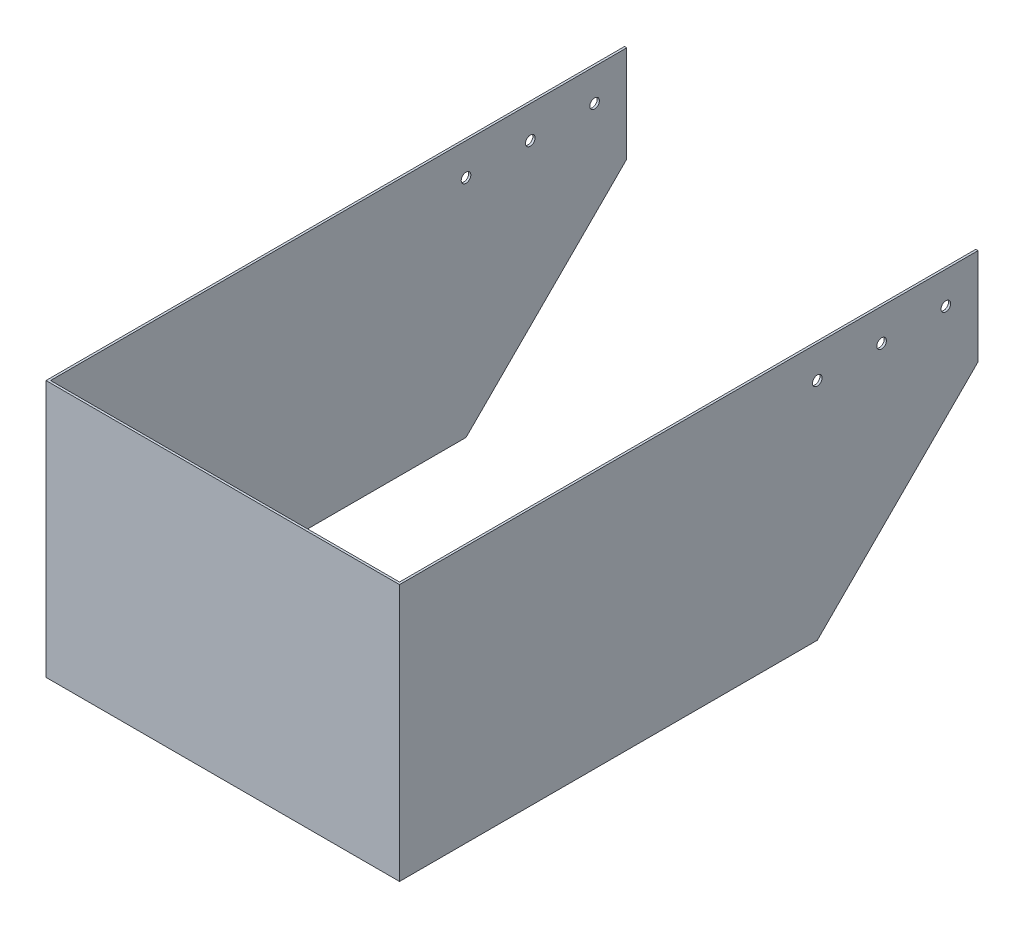
SolidWorks part; units mm, degrees
ref_plane "Front Plane" through (0, 0, 0) normal (0, 0, 1) x (1, 0, 0)
ref_plane "Top Plane" through (0, 0, 0) normal (0, 1, 0) x (1, 0, 0)
ref_plane "Right Plane" through (0, 0, 0) normal (1, 0, 0) x (0, 0, -1)
sketch "Sketch1" plane through (0, 0, 0) normal (0, 1, 0) x (1, 0, 0)
  line L1 (0, 0) -> (110, 0)
  line L2 (0, 0) -> (0, 180)
  line L3 (0, 180) -> (110, 180)
  line L4 (110, 0) -> (110, 180)
  dimension "D1" = 110
  dimension "D2" = 180
extrude "Boss-Extrude1" add sketch "Sketch1" along normal blind 80
sketch "Sketch2" plane through (0, 80, 0) normal (0, 1, 0) x (1, 0, 0)
  line L0 (110, 180) -> (0, 180) construction
  line L1 (0.7, 180) -> (109.3, 180)
  line L2 (0.7, 180) -> (0.7, 0.7)
  line L3 (0.7, 0.7) -> (109.3, 0.7)
  line L4 (109.3, 180) -> (109.3, 0.7)
  line L6 (0, 0) -> (110, 0) construction
  line L7 (0, 180) -> (0, 0) construction
  line L8 (110, 0) -> (110, 180) construction
  dimension "D1" = 0.7
  dimension "D2" = 0.7
  dimension "D3" = 0.7
extrude "Cut-Extrude1" cut sketch "Sketch2" against normal through all
sketch "Sketch4" plane through (110, 0, 0) normal (1, 0, 0) x (0, 0, -1)
  line L0 (0, 80) -> (180, 80) construction
  line L1 (180, 80) -> (180, 0) construction
  line L2 (170, 70) -> (139.2817, 70) construction
  circle A0 centre (170, 70) radius 1.5
  circle A1 centre (130, 70) radius 1.5
  circle A2 centre (150, 70) radius 1.5
  point P12 (0, 0)
  point P13 (0, 0)
  point P14 (0, 0)
  point P15 (0, 0)
  dimension "D2" = 3
  dimension "D4" = 20
  dimension "D1" = 10
  dimension "D3" = 10
  dimension "D5" = 20
extrude "Cut-Extrude3" cut sketch "Sketch4" against normal through all
sketch "Sketch8" plane through (110, 0, 0) normal (1, 0, 0) x (0, 0, -1)
  line L0 (180, 50) -> (130, 0)
  line L1 (180, 80) -> (180, 0) construction
  line L2 (0, 0) -> (180, 0) construction
  line L3 (180, 50) -> (180, 0)
  line L4 (180, 0) -> (130, 0)
  dimension "D1" = 50
  dimension "D2" = 50
extrude "Cut-Extrude5" cut sketch "Sketch8" against normal through all
